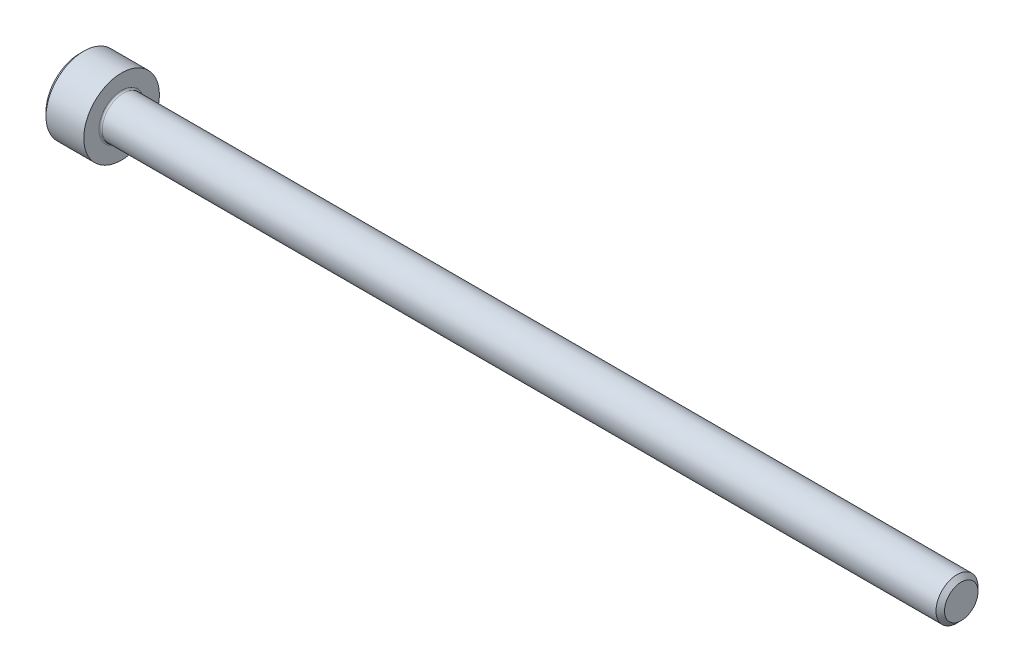
SolidWorks part; units mm, degrees
revolve "Base-Revolve" add sketch "BodySke"
sketch "BodySke" plane through (0, 0, 0) normal (0, 0, 1) x (1, 0, 0)
  line L0 (0, 0) -> (0, 2)
  line L1 (0.25, 2.25) -> (2.5, 2.25)
  line L2 (2.5, 2.25) -> (2.5, 1.25)
  line L3 (2.5, 1.25) -> (52.2465, 1.25)
  line L4 (52.5, 0.9965) -> (52.5, 0)
  line L5 (52.5, 0) -> (0, 0)
  line L6 (-31.75, 0) -> (127, 0) construction
  line L7 (0, 2) -> (0.25, 2.25)
  line L8 (52.5, 0.9965) -> (52.2465, 1.25)
  line L9 (0, -2) -> (0.25, -2.25) construction
  line L10 (52.5, -0.9965) -> (52.2465, -1.25) construction
  line L11 (2.95, 9.525) -> (2.95, 3.175) construction
  line L12 (35.5, 9.525) -> (35.5, 3.175) construction
  line L13 (2.5, 9.525) -> (2.5, 3.175) construction
  dimension "Diameter" = 2.5
  dimension "Head_ht" = 2.5
  dimension "Length" = 50
  dimension "Body_ch_ang" = 45
  dimension "Head_dia" = 4.5
  dimension "Head_ch_ang" = 45
  dimension "Minor_dia" = 1.993
  dimension "Advance" = 0.45
  dimension "Thread_nom" = 17
  dimension "Thread_length" = 50
  dimension "Head_ch_ht" = 0.25
cosmetic thread "ThreadCosmetic" [suppressed]
fillet "Fillet1" radius 0.1 1 edges at (2.5, 0, 1.25)
ref_plane "Plane1" through (0, 0, 0) normal (0, 0, 1) x (1, 0, 0)
ref_plane "Plane2" through (0, 0, 0) normal (0, 1, 0) x (1, 0, 0)
ref_plane "Plane3" through (0, 0, 0) normal (1, 0, 0) x (0, 0, -1)
other "Configuration Table"
sketch "Sketch2" plane through (0, 0, 0) normal (0, 0, 1) x (1, 0, 0)
  line L0 (0, 1.0225) -> (1.1, 1.0225)
  line L1 (1.1, 1.0225) -> (1.6903, 0)
  line L2 (-31.75, 0) -> (127, 0) construction
  line L3 (1.6903, 0) -> (0, 0)
  line L4 (0, 0) -> (0, 1.0225)
  line L5 (0, 2) -> (0, -2) construction
  line L6 (0, 0) -> (47.625, 0) construction
  line L7 (2.5, -2.25) -> (2.5, 2.25) construction
  dimension "D2" = 60
revolve "Hex-PreBroach" cut sketch "Sketch2" angle 360 about L6
sketch "Sketch3" plane through (0, 0, 0) normal (-1, 0, 0) x (0, 0.5, 0.866)
  line L0 (0.5903, 1.0225) -> (-0.5903, 1.0225)
  line L1 (-0.5903, 1.0225) -> (-1.1807, 0)
  line L2 (0.5903, 1.0225) -> (1.1807, 0)
  line L3 (0.5903, -1.0225) -> (1.1807, 0)
  line L4 (0.5903, -1.0225) -> (-0.5903, -1.0225)
  line L5 (-0.5903, -1.0225) -> (-1.1807, 0)
extrude "Hex" cut sketch "Sketch3" against normal blind 1.1
sketch "Sketch4" plane through (0, 0, 0) normal (-1, 0, 0) x (0, 0, 1)
  line L0 (0, 0) -> (1.2446, 0)
  line L1 (0, 0) -> (6.1484, 3.5498) construction
  line L2 (0, 0) -> (0.6223, 1.0779)
  line L3 (1.0085, 0.2596) -> (1.19, 0.3644)
  line L4 (0.7291, 0.7436) -> (0.9106, 0.8484)
  arc A0 (1.0085, 0.2596) -> (0.7291, 0.7436) centre (0, 0) ccw
  arc A1 (1.2446, 0) -> (1.19, 0.3644) centre (0, 0) ccw
  arc A2 (0.6223, 1.0779) -> (0.9106, 0.8484) centre (0, 0) cw
  dimension "D1" = 30
  dimension "D2" = 60
extrude "Spline" [suppressed] cut sketch "Sketch4" against normal blind 1.1
pattern_circular "CirPattern1" [suppressed] count 6 every 60
sketch "Sketch5" plane through (0, 0, 0) normal (0, 0, 1) x (1, 0, 0)
  line L0 (-31.75, 0) -> (127, 0) construction
  line L2 (0, 2) -> (0, -2) construction
  circle A0 centre (0.1, 0) radius 0.005
  dimension "Drilled_hole_dia" = 0.01
  dimension "Drilled_hole_loc" = 0.1
extrude "Hole" [suppressed] cut sketch "Sketch5" against normal through all and the other way through all
pattern_circular "Drilled-4" [suppressed] count 2 every 60
pattern_circular "Drilled-6" [suppressed] count 3 every 60
sketch "ThdSchSke" plane through (0, 0, 0) normal (0, 0, 1) x (1, 0, 0)
  line L0 (35.5, -0.9965) -> (35.3225, -1.25)
  line L1 (35.5, -0.9965) -> (35.6775, -1.25)
  line L2 (35.6775, -1.25) -> (35.6775, -1.5625)
  line L3 (-3.175, 0) -> (5.1513, 0) construction
  line L5 (35.6775, -1.5625) -> (35.3225, -1.5625)
  line L6 (35.3225, -1.5625) -> (35.3225, -1.25)
  line L7 (0, 2) -> (0, -2) construction
revolve "ThreadSchematic" [suppressed] cut sketch "ThdSchSke" angle 360 about L3
pattern_linear "ThdSchPat" [suppressed]
equation "\"D2@Sketch3\" = \"Hex_size@Sketch3\" / 2"
equation "\"D1@Sketch3\" = \"Hex_size@Sketch3\" / 2"
equation "\"D1@Sketch2\" = \"Hex_size@Sketch3\" / 2"
equation "\"D3@Sketch4\" = \"Spline_p_dim@Sketch4\" / 2"
equation "\"Thread_minor@ThreadCosmetic\"  =  \"Minor_dia@BodySke\""
equation "\"D2@CirPattern1\" = 360 / \"Num_teeth@CirPattern1\""
equation "\"Wall_thickness@Sketch2\" = \"Head_ht@BodySke\" - \"Key_eng@Hex\""
equation "\"Thread_length@ThreadCosmetic\" = ((sgn( (\"Length@BodySke\" - \"Advance@BodySke\" ) - \"Thread_nom@BodySke\" )-1)*( (\"Length@BodySke\" - \"Advance@BodySke\" ) - \"Thread_nom@BodySke\" ))/-2+ \"Thread_nom@BodySke\""
equation "\"Thread_minor@ThdSchSke\" = \"Minor_dia@BodySke\""
equation "\"Diameter@ThdSchSke\" = \"Diameter@BodySke\""
equation "\"Overcut@ThdSchSke\" = \"Diameter@BodySke\" * 1.25"
equation "\"Start@ThdSchSke\" = \"Head_ht@BodySke\" + \"Length@BodySke\" - \"Thread_length@ThreadCosmetic\"  '---Non-countersunk---"
equation "\"Num_threads@ThdSchPat\" = int( \"Thread_length@ThreadCosmetic\" / \"Advance@BodySke\" + 0.999 )  + 1"
equation "\"Advance@ThdSchPat\" = \"Thread_length@ThreadCosmetic\" /  (\"Num_threads@ThdSchPat\" - 1) 'relax it"
equation "\"Num_threads@ThdSchPat\" = \"Num_threads@ThdSchPat\" - sgn( \"Num_threads@ThdSchPat\" - 1) '---chamfered tips only---"
